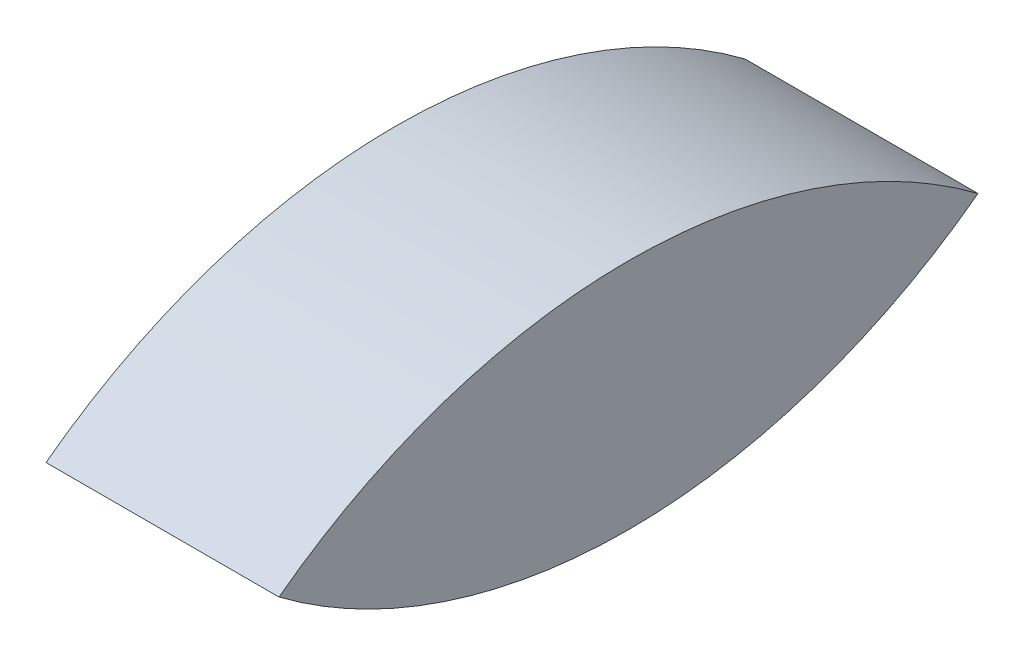
SolidWorks part; units mm, degrees
ref_plane "Спереди"
ref_plane "Сверху" through (0, 0, 0) normal (0, 1, 0) x (1, 0, 0)
ref_plane "Справа" through (0, 0, 0) normal (1, 0, 0) x (0, 0, -1)
sketch "Эскиз3" plane through (0, 0, 0) normal (1, 0, 0) x (0, 0, -1)
  line L0 (0, 0) -> (0, 5) construction
  line L1 (0, 5) -> (30, 5) construction
  line L2 (30, 5) -> (30, 0) construction
  line L3 (30, 0) -> (0, 0) construction
  arc A0 (0, 0) -> (30, 0) centre (15, -20) cw
  arc A1 (0, 0) -> (30, 0) centre (15, 20) ccw
  dimension "D1" = 5
  dimension "D2" = 30
extrude "Бобышка-Вытянуть1" add sketch "Эскиз3" along normal mid plane 10
